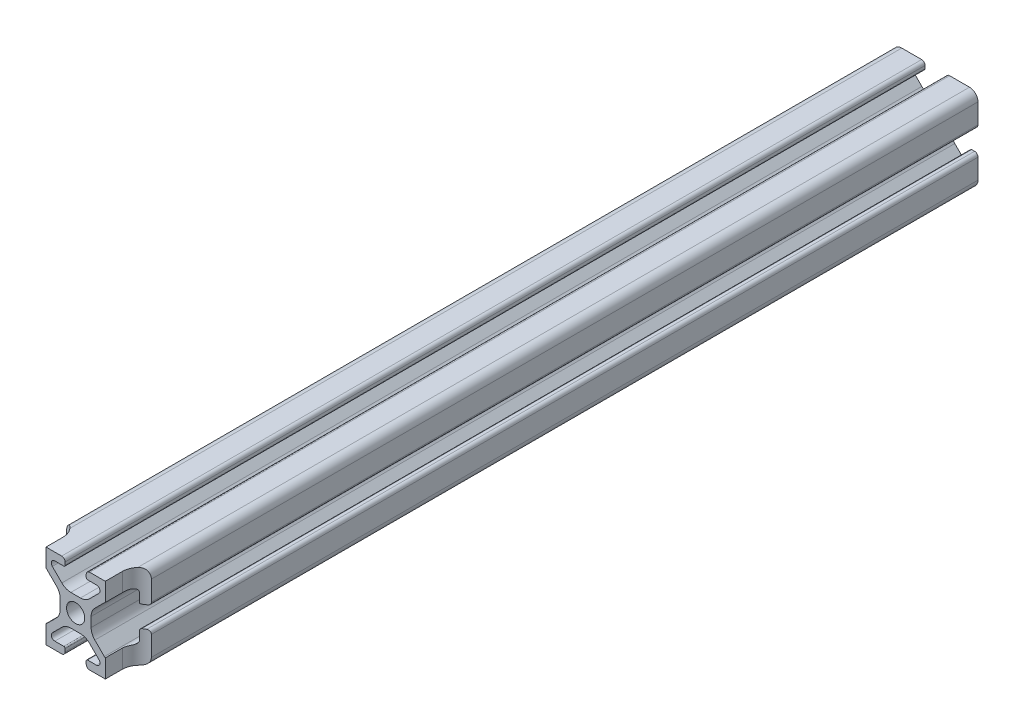
SolidWorks part; units mm, degrees
material "3.0205 (EN-AW 1200)"
ref_plane "Plan de face" through (0, 0, 0) normal (0, 0, 1) x (1, 0, 0)
ref_plane "Plan de dessus" through (0, 0, 0) normal (0, 1, 0) x (1, 0, 0)
ref_plane "Plan de droite" through (0, 0, 0) normal (1, 0, 0) x (0, 0, -1)
ref_plane "Plan1" through (0, 0, 0) normal (0, 0, -1) x (-1, 0, 0)
sketch "Esquisse1" plane through (0, 0, 0) normal (0, 0, -1) x (-1, 0, 0)
  line L0 (-12.5, 0.8) -> (-12.5, 1.5)
  line L1 (-12.8, 1.8) -> (-14.9176, 1.8)
  line L2 (-15.5062, 3.221) -> (-13.2559, 5.4713)
  line L3 (-11.1346, 6.35) -> (-8.8654, 6.35)
  line L4 (-6.7441, 5.4713) -> (-4.4938, 3.221)
  line L5 (-5.0824, 1.8) -> (-7.2, 1.8)
  line L6 (-7.5, 1.5) -> (-7.5, 0.8)
  line L7 (-6.7, 0) -> (-2, 0)
  line L8 (0, 2) -> (0, 6.7)
  line L9 (-0.8, 7.5) -> (-1.5, 7.5)
  line L10 (-1.8, 7.2) -> (-1.8, 5.0824)
  line L11 (-3.221, 4.4938) -> (-5.4713, 6.7441)
  line L12 (-6.35, 8.8654) -> (-6.35, 11.1346)
  line L13 (-5.4713, 13.2559) -> (-3.221, 15.5062)
  line L14 (-1.8, 14.9176) -> (-1.8, 12.8)
  line L15 (-1.5, 12.5) -> (-0.8, 12.5)
  line L16 (0, 13.3) -> (0, 18)
  line L17 (-2, 20) -> (-6.7, 20)
  line L18 (-7.5, 19.2) -> (-7.5, 18.5)
  line L19 (-7.2, 18.2) -> (-5.0824, 18.2)
  line L20 (-4.4938, 16.779) -> (-6.7441, 14.5287)
  line L21 (-8.8654, 13.65) -> (-11.1346, 13.65)
  line L22 (-13.2559, 14.5287) -> (-15.5062, 16.779)
  line L23 (-14.9176, 18.2) -> (-12.8, 18.2)
  line L24 (-12.5, 18.5) -> (-12.5, 19.2)
  line L25 (-13.3, 20) -> (-18, 20)
  line L26 (-20, 18) -> (-20, 13.3)
  line L27 (-19.2, 12.5) -> (-18.5, 12.5)
  line L28 (-18.2, 12.8) -> (-18.2, 14.9176)
  line L29 (-16.779, 15.5062) -> (-14.5287, 13.2559)
  line L30 (-13.65, 11.1346) -> (-13.65, 8.8654)
  line L31 (-14.5287, 6.7441) -> (-16.779, 4.4938)
  line L32 (-18.2, 5.0824) -> (-18.2, 7.2)
  line L33 (-18.5, 7.5) -> (-19.2, 7.5)
  line L34 (-20, 6.7) -> (-20, 2)
  line L35 (-18, 0) -> (-13.3, 0)
  arc A0 (-12.5, 1.5) -> (-12.8, 1.8) centre (-12.8, 1.5) ccw
  arc A1 (-14.9176, 1.8) -> (-15.5062, 3.221) centre (-14.9176, 2.6324) cw
  arc A2 (-13.2559, 5.4713) -> (-11.1346, 6.35) centre (-11.1346, 3.35) cw
  arc A3 (-8.8654, 6.35) -> (-6.7441, 5.4713) centre (-8.8654, 3.35) cw
  arc A4 (-4.4938, 3.221) -> (-5.0824, 1.8) centre (-5.0824, 2.6324) cw
  arc A5 (-7.2, 1.8) -> (-7.5, 1.5) centre (-7.2, 1.5) ccw
  arc A6 (-7.5, 0.8) -> (-6.7, 0) centre (-6.7, 0.8) ccw
  arc A7 (-2, 0) -> (0, 2) centre (-2, 2) ccw
  arc A8 (0, 6.7) -> (-0.8, 7.5) centre (-0.8, 6.7) ccw
  arc A9 (-1.5, 7.5) -> (-1.8, 7.2) centre (-1.5, 7.2) ccw
  arc A10 (-1.8, 5.0824) -> (-3.221, 4.4938) centre (-2.6324, 5.0824) cw
  arc A11 (-5.4713, 6.7441) -> (-6.35, 8.8654) centre (-3.35, 8.8654) cw
  arc A12 (-6.35, 11.1346) -> (-5.4713, 13.2559) centre (-3.35, 11.1346) cw
  arc A13 (-3.221, 15.5062) -> (-1.8, 14.9176) centre (-2.6324, 14.9176) cw
  arc A14 (-1.8, 12.8) -> (-1.5, 12.5) centre (-1.5, 12.8) ccw
  arc A15 (-0.8, 12.5) -> (0, 13.3) centre (-0.8, 13.3) ccw
  arc A16 (0, 18) -> (-2, 20) centre (-2, 18) ccw
  arc A17 (-6.7, 20) -> (-7.5, 19.2) centre (-6.7, 19.2) ccw
  arc A18 (-7.5, 18.5) -> (-7.2, 18.2) centre (-7.2, 18.5) ccw
  arc A19 (-5.0824, 18.2) -> (-4.4938, 16.779) centre (-5.0824, 17.3676) cw
  arc A20 (-6.7441, 14.5287) -> (-8.8654, 13.65) centre (-8.8654, 16.65) cw
  arc A21 (-11.1346, 13.65) -> (-13.2559, 14.5287) centre (-11.1346, 16.65) cw
  arc A22 (-15.5062, 16.779) -> (-14.9176, 18.2) centre (-14.9176, 17.3676) cw
  arc A23 (-12.8, 18.2) -> (-12.5, 18.5) centre (-12.8, 18.5) ccw
  arc A24 (-12.5, 19.2) -> (-13.3, 20) centre (-13.3, 19.2) ccw
  arc A25 (-18, 20) -> (-20, 18) centre (-18, 18) ccw
  arc A26 (-20, 13.3) -> (-19.2, 12.5) centre (-19.2, 13.3) ccw
  arc A27 (-18.5, 12.5) -> (-18.2, 12.8) centre (-18.5, 12.8) ccw
  arc A28 (-18.2, 14.9176) -> (-16.779, 15.5062) centre (-17.3676, 14.9176) cw
  arc A29 (-14.5287, 13.2559) -> (-13.65, 11.1346) centre (-16.65, 11.1346) cw
  arc A30 (-13.65, 8.8654) -> (-14.5287, 6.7441) centre (-16.65, 8.8654) cw
  arc A31 (-16.779, 4.4938) -> (-18.2, 5.0824) centre (-17.3676, 5.0824) cw
  arc A32 (-18.2, 7.2) -> (-18.5, 7.5) centre (-18.5, 7.2) ccw
  arc A33 (-19.2, 7.5) -> (-20, 6.7) centre (-19.2, 6.7) ccw
  arc A34 (-20, 2) -> (-18, 0) centre (-18, 2) ccw
  arc A35 (-13.3, 0) -> (-12.5, 0.8) centre (-13.3, 0.8) ccw
  circle A36 centre (-10, 10) radius 2.15
extrude "Boss.-Extru.1" add sketch "Esquisse1" against normal blind 203
sketch "Esquisse2" plane through (0, 20, 0) normal (0, 1, 0) x (1, 0, 0)
  line L0 (21, -199) -> (21, -209) construction
  line L2 (25, -199) -> (25, -209)
  line L3 (17, -199) -> (17, -209)
  line L4 (20, -203) -> (20, 0) construction
  line L5 (10, -203) -> (10, -193) construction
  line L6 (8.8654, -203) -> (11.1346, -203) construction
  line L7 (-1, -199) -> (-1, -209) construction
  line L8 (-5, -199) -> (-5, -209)
  line L9 (3, -199) -> (3, -209)
  line L11 (13.3, -203) -> (18, -203) construction
  arc A1 (25, -199) -> (17, -199) centre (21, -199) ccw
  arc A2 (17, -209) -> (25, -209) centre (21, -209) ccw
  arc A3 (-5, -199) -> (3, -199) centre (-1, -199) cw
  arc A4 (3, -209) -> (-5, -209) centre (-1, -209) cw
  point P2 (22, -211.4213)
  point P3 (0, 0)
  point P4 (21, -204)
  point P11 (-1, -204)
  point P24 (0, 0)
  dimension "D1" = 3
  dimension "D4" = 8
  dimension "D2" = 8
  dimension "D3" = 10
extrude "Enlèv. mat.-Extru.1" cut sketch "Esquisse2" against normal through all
